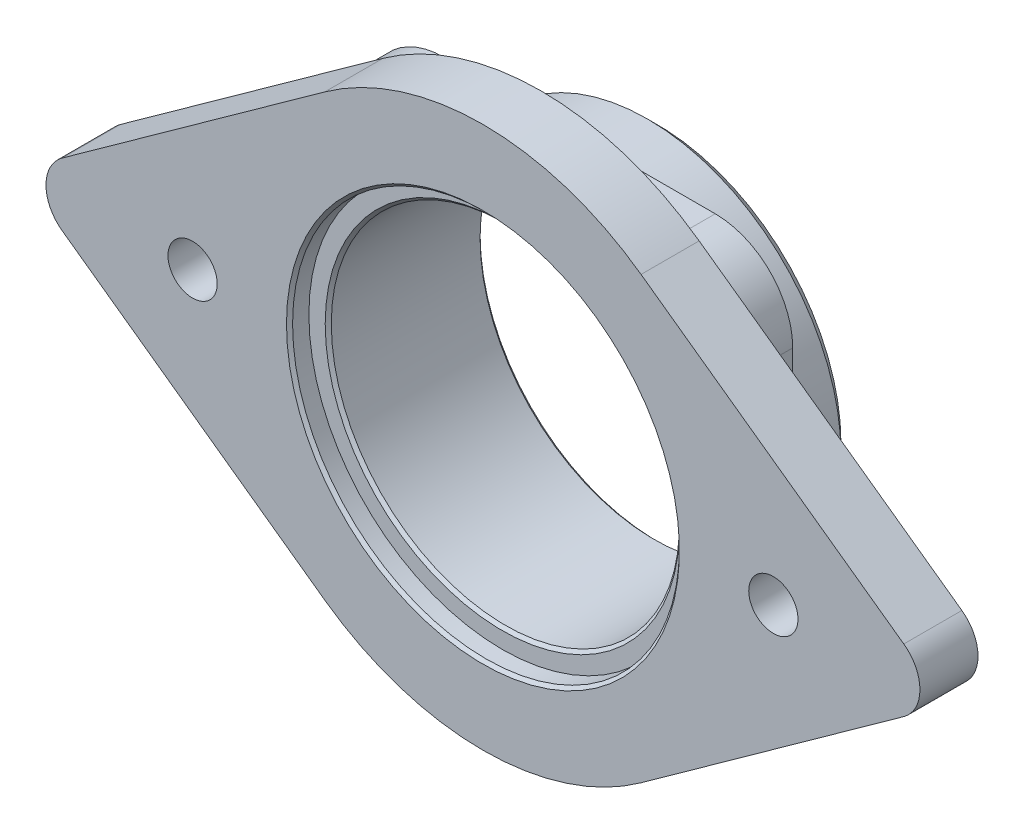
SolidWorks part; units mm, degrees
material "6061-T6 (SS)"
ref_plane "Front Plane" through (0, 0, 0) normal (0, 0, 1) x (1, 0, 0)
ref_plane "Top Plane" through (0, 0, 0) normal (0, 1, 0) x (1, 0, 0)
ref_plane "Right Plane" through (0, 0, 0) normal (1, 0, 0) x (0, 0, -1)
ref_plane "Plane1" through (0, 0, -2.3813) normal (0, 0, -1) x (-1, 0, 0)
sketch "Sketch1" plane through (0, 0, -2.3813) normal (0, 0, -1) x (-1, 0, 0)
  line L0 (-34.5092, -2.5788) -> (0, -27.3628)
  line L1 (0, -27.3628) -> (34.5092, -2.5788)
  line L2 (34.5092, 2.5788) -> (0, 27.3628)
  line L3 (0, 27.3628) -> (-34.5092, 2.5788)
  arc A0 (-34.5092, 2.5788) -> (-34.5092, -2.5788) centre (-32.6571, 0) ccw
  arc A1 (34.5092, -2.5788) -> (34.5092, 2.5788) centre (32.6571, 0) ccw
  point P8 (35.8321, 0)
  point P9 (-35.8321, 0)
  dimension "D1" = 71.6643
extrude "Boss-Extrude1" add sketch "Sketch1" against normal blind 4.7625
sketch "Sketch2" plane through (0, 0, -2.3813) normal (0, 0, -1) x (-1, 0, 0)
  line L0 (-17.4625, -11.1125) -> (-17.4625, 11.1125)
  line L1 (-11.1125, 17.4625) -> (11.1125, 17.4625)
  line L2 (17.4625, 11.1125) -> (17.4625, -11.1125)
  line L3 (11.1125, -17.4625) -> (-11.1125, -17.4625)
  arc A0 (-17.4625, 11.1125) -> (-11.1125, 17.4625) centre (-11.1125, 11.1125) cw
  arc A1 (11.1125, 17.4625) -> (17.4625, 11.1125) centre (11.1125, 11.1125) cw
  arc A2 (17.4625, -11.1125) -> (11.1125, -17.4625) centre (11.1125, -11.1125) cw
  arc A3 (-11.1125, -17.4625) -> (-17.4625, -11.1125) centre (-11.1125, -11.1125) cw
  dimension "D1" = 6.35
  dimension "D2" = 34.925
  dimension "D3" = 34.925
extrude "Boss-Extrude2" add sketch "Sketch2" along normal blind 3.175
sketch "Sketch3" plane through (0, 0, 0) normal (0, 1, 0) x (1, 0, 0)
  line L0 (15.8623, 11.9062) -> (0, 11.9062)
  line L1 (0, 11.9062) -> (0, 5.5563)
  line L2 (0, 5.5563) -> (15.8623, 5.5563)
  line L3 (15.8623, 5.5563) -> (15.8623, 11.9062)
  line L4 (0, 11.9062) -> (0, 5.5563) construction
revolve "Revolve1" add sketch "Sketch3" angle 360 about L4
hole_wizard "M3.5 Clearance Hole1" positions "Sketch5" profile "Sketch4" hole size "M3.5" standard "ANSI Metric" end condition through all
sketch "Sketch5" plane through (0, 0, -2.3813) normal (0, 0, -1) x (-1, 0, 0)
  point P0 (23.8125, 0)
  point P1 (-23.8125, 0)
sketch "Sketch4" plane through (-23.8125, 0, -2.3813) normal (1, 0, 0) x (0, 1, 0)
  line L0 (0, 0) -> (0, 4.7625)
  line L1 (0, 4.7625) -> (2.0193, 4.7625)
  line L2 (2.0193, 4.7625) -> (2.0193, 0)
  line L5 (2.0193, 0) -> (0, 0)
  line L11 (0, -6.35) -> (0, 107.95) construction
  dimension "Thru Hole Dia." = 4.0386
  dimension "Thru Hole Depth" = 4.7625
hole_wizard "CBORE for M25 SHSS1" positions "Sketch7" profile "Sketch6" counterbore size "M25" standard "ANSI Metric"
sketch "Sketch7" plane through (0, 0, 2.3813) normal (0, 0, 1) x (1, 0, 0)
  point P0 (0, 0)
sketch "Sketch6" plane through (0, 0, 2.3813) normal (1, 0, 0) x (0, -1, 0)
  line L0 (0, 0) -> (0, 14.2875)
  line L1 (0, 14.2875) -> (14.2748, 14.2875)
  line L3 (14.2748, 14.2875) -> (14.2748, 1.5875)
  line L4 (14.2748, 1.5875) -> (15.8623, 1.5875)
  line L5 (15.8623, 1.5875) -> (15.8623, 0)
  line L7 (15.8623, 0) -> (0, 0)
  line L11 (0, -6.35) -> (0, 107.95) construction
  dimension "Thru Hole Dia." = 28.5496
  dimension "Thru Hole Depth" = 14.2875
  dimension "C'Bore Dia." = 31.7246
  dimension "C'Bore Depth" = 1.5875
chamfer "Chamfer1" distance 0.25 angle 45 3 edges at (14.2748, 0, -11.9063) (14.2748, 0, 0.7938) (15.8623, 0, 2.3813)
chamfer "Chamfer2" distance 0.7937 angle 45 1 edges at (15.8623, 0, -11.9062)
fillet "Fillet1" radius 22.225 2 edges at (0, -27.3628, 0) (0, 27.3628, 0)
